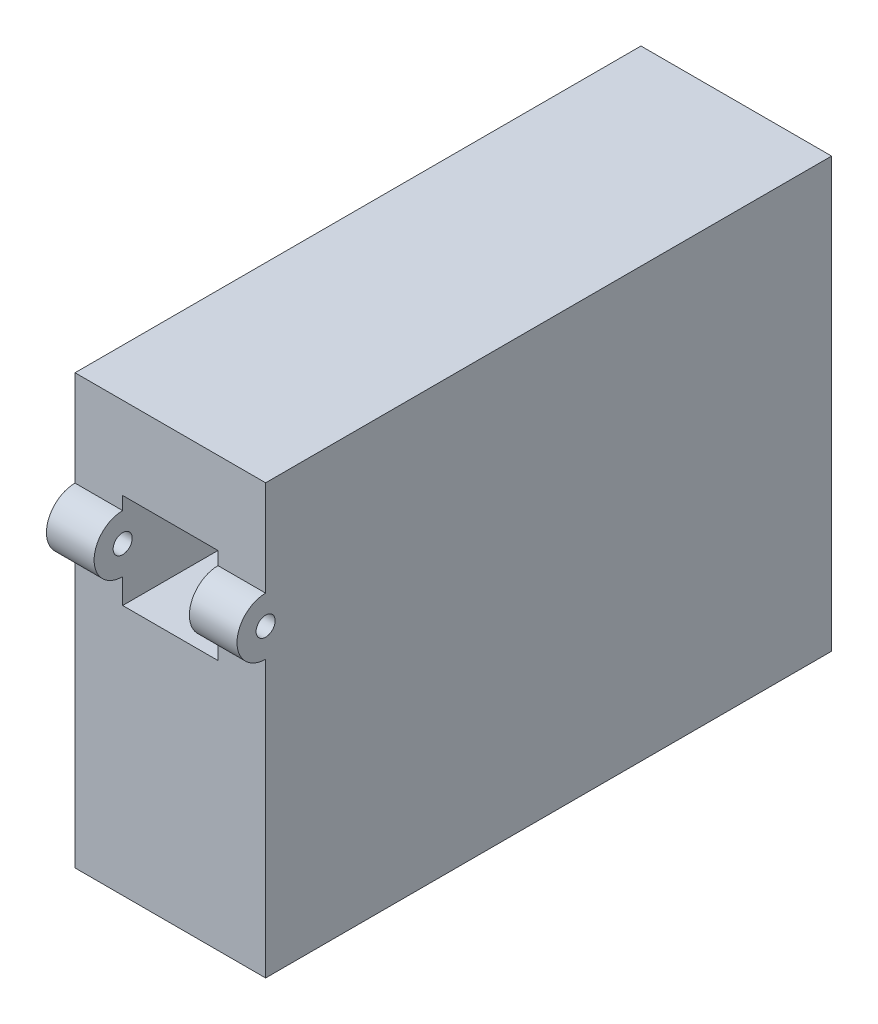
SolidWorks part; units mm, degrees
ref_plane "Front Plane" through (0, 0, 0) normal (0, 0, 1) x (1, 0, 0)
ref_plane "Top Plane" through (0, 0, 0) normal (0, 1, 0) x (1, 0, 0)
ref_plane "Right Plane" through (0, 0, 0) normal (1, 0, 0) x (0, 0, -1)
sketch "Sketch5" plane through (0.3236, 0, -7.846) normal (0, 1, 0) x (1, 0, 0)
  line L0 (-55.0619, 46.1644) -> (-35.0619, 46.1644)
  line L1 (-35.0619, 46.1644) -> (-35.0619, -13.2186)
  line L2 (-35.0619, -13.2186) -> (-55.0619, -13.2186)
  line L3 (-55.0619, 46.1644) -> (-55.0619, -13.2186)
extrude "Boss-Extrude2" add sketch "Sketch5" along normal blind 50 and the other way blind 0.0001
sketch "Sketch6" plane through (0.3236, 50, -7.846) normal (0, 1, 0) x (1, 0, 0)
  circle A0 centre (-45.0619, 16.5749) radius 5
extrude "Cut-Extrude1" cut sketch "Sketch6" against normal blind 45 contours A0
sketch "Sketch9" plane through (0.3236, 0, 5.3726) normal (0, 0, 1) x (1, 0, 0)
  line L4 (-50.0619, 41.3488) -> (-40.0619, 41.3488)
  line L6 (-40.0619, 41.3488) -> (-40.0619, 31.3488)
  line L7 (-40.0619, 31.3488) -> (-50.0619, 31.3488)
  line L8 (-50.0619, 31.3488) -> (-50.0619, 41.3488)
extrude "Cut-Extrude4" cut sketch "Sketch9" against normal blind 0.0768
sketch "Sketch10" plane through (-34.7383, 0, -7.846) normal (1, 0, 0) x (0, 0, -1)
  line L0 (-13.2186, 41.3488) -> (-13.2186, 38.972)
  line L1 (-13.2186, 50) -> (-13.2186, -0.0001) construction
  line L2 (-13.2186, 38.972) -> (-13.2186, 34.972)
  line L3 (-13.2186, 37.9574) -> (-13.2186, 35.9866)
  arc A0 (-13.2186, 38.972) -> (-13.2186, 34.972) centre (-13.2186, 36.972) ccw
  arc A1 (-13.2186, 37.9574) -> (-13.2186, 35.9866) centre (-13.2186, 36.972) ccw
extrude "Boss-Extrude5" add sketch "Sketch10" against normal blind 5 contours A0 L2
sketch "Sketch12" plane through (-34.7383, 0, -7.846) normal (1, 0, 0) x (0, 0, -1)
  line L0 (-13.2186, 37.972) -> (-13.2186, 35.972)
  line L1 (-13.2186, 37.972) -> (-13.2186, 38.972)
  line L2 (-13.2186, 35.972) -> (-13.2186, 34.972)
  arc A0 (-13.2186, 37.972) -> (-13.2186, 35.972) centre (-13.2186, 36.972) ccw
extrude "Cut-Extrude6" cut sketch "Sketch12" against normal blind 5 contours A0 L0
sketch "Sketch14" plane through (-54.7383, 0, -7.846) normal (-1, 0, 0) x (0, 0, 1)
  line L2 (13.2186, 37.972) -> (13.2186, 38.972)
  line L3 (13.2186, 35.972) -> (13.2186, 34.972)
  arc A0 (13.2186, 34.972) -> (13.2186, 38.972) centre (13.2186, 36.972) ccw
  arc A1 (13.2186, 35.972) -> (13.2186, 37.972) centre (13.2186, 36.972) ccw
extrude "Boss-Extrude6" add sketch "Sketch14" against normal blind 5
sketch "Sketch15" plane through (-34.7383, 0, -7.846) normal (1, 0, 0) x (0, 0, -1)
  line L0 (-13.2186, 37.972) -> (-13.2186, 35.972) construction
  circle A0 centre (-13.2186, 36.972) radius 1
extrude "Cut-Extrude7" cut sketch "Sketch15" against normal blind 20
sketch "Sketch19" plane through (0.3236, 50, -7.846) normal (0, 1, 0) x (1, 0, 0)
  circle A0 centre (-45.0619, 16.5749) radius 5
extrude "Boss-Extrude13" add sketch "Sketch19" against normal blind 45
ref_plane "Plane1" through (-54.7383, 34.972, 5.3726) normal (0, 0, 1) x (1, 0, 0)
sketch "Sketch21" plane through (-34.7383, 0, -7.846) normal (1, 0, 0) x (0, 0, -1)
  line L2 (-13.2186, 39.972) -> (-13.2186, 37.972)
  line L3 (-13.2186, 33.972) -> (-13.2186, 35.972)
  arc A0 (-13.2186, 39.972) -> (-13.2186, 33.972) centre (-13.2186, 36.972) ccw
  circle A2 centre (-13.2186, 36.972) radius 1 construction
  circle A4 centre (-13.2186, 36.972) radius 1
  arc A5 (-13.2186, 35.972) -> (-13.2186, 37.972) centre (-13.2186, 36.972) ccw
  dimension "D1" = 0
extrude "Boss-Extrude15" add sketch "Sketch21" against normal blind 5
sketch "Sketch22" plane through (-34.7383, 0, -7.846) normal (1, 0, 0) x (0, 0, -1)
  circle A0 centre (-13.2186, 36.972) radius 1
extrude "Cut-Extrude8" cut sketch "Sketch22" against normal blind 5
sketch "Sketch23" plane through (-54.7383, 0, -7.846) normal (-1, 0, 0) x (0, 0, 1)
  line L0 (13.2186, 39.972) -> (13.2186, 37.972)
  line L1 (13.2186, 33.972) -> (13.2186, 35.972)
  arc A0 (13.2186, 33.972) -> (13.2186, 39.972) centre (13.2186, 36.972) ccw
  circle A1 centre (13.2186, 36.972) radius 1 construction
  circle A3 centre (13.2186, 36.972) radius 1
  arc A4 (13.2186, 35.972) -> (13.2186, 37.972) centre (13.2186, 36.972) ccw
  dimension "D1" = 0
extrude "Boss-Extrude16" add sketch "Sketch23" against normal blind 5
sketch "Sketch24" plane through (0.3236, 0, -54.0104) normal (0, 0, -1) x (-1, 0, 0)
  line L10 (53.055, 10.016) -> (53.055, 46)
  line L11 (37.0619, 46) -> (37.0619, 10.016)
  line L12 (37.0619, 10.016) -> (53.055, 10.016)
  line L13 (37.0619, 46) -> (53.055, 46)
extrude "Cut-Extrude9" cut sketch "Sketch24" against normal blind 36
sketch "Sketch26" plane through (0.3236, 0, 5.2958) normal (0, 0, 1) x (1, 0, 0)
  line L0 (-50.0619, 41.3488) -> (-40.0619, 41.3488)
  line L1 (-40.0619, 41.3488) -> (-40.0619, 31.3488)
  line L2 (-40.0619, 31.3488) -> (-50.0619, 31.3488)
  line L3 (-50.0619, 31.3488) -> (-50.0619, 41.3488)
extrude "Cut-Extrude13" cut sketch "Sketch26" against normal blind 36
sketch "Sketch28" plane through (0, -0.0001, -2.542) normal (0, -1, 0) x (-1, 0, 0)
  line L0 (54.7383, -7.9145) -> (34.7383, -7.9145)
  line L1 (34.7383, -7.9145) -> (34.7383, 31.7533)
  line L2 (34.7383, 31.7533) -> (54.7383, 31.879)
  line L3 (54.7383, 31.879) -> (54.7383, -7.9145)
extrude "Cut-Extrude14" cut sketch "Sketch28" against normal blind 5
sketch "Sketch29" plane through (0.1981, 0, -34.0757) normal (-0.0063, 0, 1) x (1, 0, 0.0063)
  line L0 (-54.9375, 4.9999) -> (-34.9371, 4.9999)
  line L1 (-34.9371, 4.9999) -> (-34.9371, -0.0001)
  line L2 (-34.9371, -0.0001) -> (-54.9375, -0.0001)
  line L3 (-54.9375, -0.0001) -> (-54.9375, 4.9999)
extrude "Cut-Extrude15" cut sketch "Sketch29" against normal blind 1
sketch "Sketch31" plane through (0, 4.9999, -2.542) normal (0, -1, 0) x (-1, 0, 0)
  circle A0 centre (44.7383, 11.9822) radius 3
extrude "Cut-Extrude16" cut sketch "Sketch31" against normal blind 3
sketch "Sketch32" plane through (0.2204, 0, -35.0756) normal (-0.0063, 0, 1) x (1, 0, 0.0063)
  line L0 (-54.9535, 4.9999) -> (-34.9594, 4.9999)
  line L1 (-34.9594, 4.9999) -> (-34.9594, -0.0001)
  line L2 (-34.9594, -0.0001) -> (-54.9535, -0.0001)
  line L3 (-54.9535, -0.0001) -> (-34.9594, -0.0001) construction
  line L4 (-54.9535, 4.9999) -> (-54.9535, -0.0001) construction
  line L5 (-54.9535, -0.0001) -> (-54.9535, 4.9999)
extrude "Cut-Extrude17" cut sketch "Sketch32" against normal blind 19
sketch "Sketch33" plane through (-54.7383, 0, 0) normal (-1, 0, 0) x (0, 0, 1)
  line L0 (-34.4209, 4.9999) -> (-54.0104, 4.9999)
  line L1 (-54.0104, -0.0001) -> (-54.0104, 50) construction
  line L2 (-54.0104, 4.9999) -> (-54.0104, -0.0001)
  line L3 (-54.0104, -0.0001) -> (-34.4209, -0.0001)
  line L4 (-34.4209, -0.0001) -> (-34.4209, 4.9999)
extrude "Cut-Extrude18" cut sketch "Sketch33" against normal blind 19
